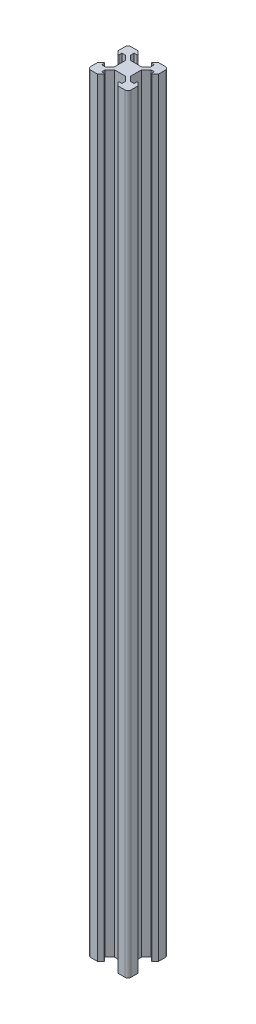
SolidWorks part; units mm, degrees
ref_plane "Спереди" through (0, 0, 0) normal (0, 0, 1) x (1, 0, 0)
ref_plane "Сверху" through (0, 0, 0) normal (0, 1, 0) x (1, 0, 0)
ref_plane "Справа" through (0, 0, 0) normal (1, 0, 0) x (0, 0, -1)
sketch "Эскиз1" plane through (0, 0, 0) normal (0, 1, 0) x (1, 0, 0)
  line L0 (8, 5) -> (6.2728, 5)
  line L1 (8.5, 10) -> (-8.5, 10)
  line L2 (10, 8.5) -> (10, -8.5)
  line L3 (8.5, -10) -> (-8.5, -10)
  line L4 (-10, 8.5) -> (-10, -8.5)
  line L5 (10, 10) -> (-10, -10) construction
  line L6 (10, -10) -> (-10, 10) construction
  line L7 (5, -10) -> (3.5121, -8.5121)
  line L8 (8, 5) -> (5, 5)
  line L9 (8, 5) -> (8, 3.7243)
  line L10 (8, -5) -> (6.2728, -5)
  line L11 (10, 5) -> (8.5121, 3.5121)
  line L12 (8, -5) -> (8, -3.7243)
  line L13 (10, 0) -> (-10, 0) construction
  line L14 (10, -5) -> (8.5121, -3.5121)
  line L15 (5, -8) -> (3.7243, -8)
  line L16 (5, -8) -> (5, -6.2728)
  line L17 (5, -6.2728) -> (2.7272, -4)
  line L18 (2.7272, -4) -> (-2.7272, -4)
  line L19 (-2.7272, -4) -> (-5, -6.2728)
  line L20 (-5, -8) -> (-5, -6.2728)
  line L21 (-5, -8) -> (-3.7243, -8)
  line L22 (-5, -10) -> (-3.5121, -8.5121)
  line L23 (-10, -5) -> (-8.5121, -3.5121)
  line L24 (-8, -5) -> (-8, -3.7243)
  line L25 (-8, -5) -> (-6.2728, -5)
  line L26 (-6.2728, -5) -> (-4, -2.7272)
  line L27 (-4, -2.7272) -> (-4, 2.7272)
  line L28 (-4, 2.7272) -> (-6.2728, 5)
  line L29 (-8, 5) -> (-6.2728, 5)
  line L30 (-8, 5) -> (-8, 3.7243)
  line L31 (-10, 5) -> (-8.5121, 3.5121)
  line L32 (-5, 10) -> (-3.5121, 8.5121)
  line L33 (-5, 8) -> (-3.7243, 8)
  line L34 (-5, 8) -> (-5, 6.2728)
  line L35 (-5, 6.2728) -> (-2.7272, 4)
  line L36 (6.2728, 5) -> (4, 2.7272)
  line L37 (-2.7272, 4) -> (2.7272, 4)
  line L38 (4, -2.7272) -> (6.2728, -5)
  line L39 (2.7272, 4) -> (5, 6.2728)
  line L40 (4, 2.7272) -> (4, -2.7272)
  line L41 (5, 8) -> (5, 6.2728)
  line L42 (5, 10) -> (5, 4) [skipped]
  line L43 (5, 8) -> (3, 8) [skipped]
  line L44 (5, 10) -> (3, 8) [skipped]
  line L45 (5, -10) -> (5, -4) [skipped]
  line L46 (5, -10) -> (3, -8) [skipped]
  line L47 (5, -8) -> (3, -8) [skipped]
  line L48 (-5, -10) -> (-5, -4) [skipped]
  line L49 (-5, -8) -> (-3, -8) [skipped]
  line L50 (-5, -10) -> (-3, -8) [skipped]
  line L51 (-10, -5) -> (-4, -5) [skipped]
  line L52 (-8, 5) -> (-8, 3) [skipped]
  line L53 (-10, 5) -> (-4, 5) [skipped]
  line L54 (-5, 10) -> (-5, 4) [skipped]
  line L55 (-5, 8) -> (-3, 8) [skipped]
  line L56 (-5, 10) -> (-3, 8) [skipped]
  line L57 (-10, 5) -> (-8, 3) [skipped]
  line L58 (-8, -5) -> (-8, -3) [skipped]
  line L59 (-10, -5) -> (-8, -3) [skipped]
  line L60 (5, 8) -> (3.7243, 8)
  line L61 (5, 10) -> (3.5121, 8.5121)
  arc A0 (-8.5, -10) -> (-10, -8.5) centre (-8.5, -8.5) cw
  arc A1 (-8.5, 10) -> (-10, 8.5) centre (-8.5, 8.5) ccw
  arc A2 (10, -8.5) -> (8.5, -10) centre (8.5, -8.5) cw
  arc A3 (8.5, 10) -> (10, 8.5) centre (8.5, 8.5) cw
  arc A4 (8, 3.7243) -> (8.5121, 3.5121) centre (8.3, 3.7243) ccw
  arc A5 (8, -3.7243) -> (8.5121, -3.5121) centre (8.3, -3.7243) cw
  arc A6 (-8, 3.7243) -> (-8.5121, 3.5121) centre (-8.3, 3.7243) cw
  arc A7 (-8.5121, -3.5121) -> (-8, -3.7243) centre (-8.3, -3.7243) cw
  arc A8 (-3.7243, -8) -> (-3.5121, -8.5121) centre (-3.7243, -8.3) cw
  arc A9 (3.5121, -8.5121) -> (3.7243, -8) centre (3.7243, -8.3) cw
  arc A10 (3.7243, 8) -> (3.5121, 8.5121) centre (3.7243, 8.3) cw
  arc A11 (-3.7243, 8) -> (-3.5121, 8.5121) centre (-3.7243, 8.3) ccw
  point P0 (0, 0)
  point P12 (4, 0)
  point P20 (0, 0)
  point P21 (0, 0)
  point P29 (0, 0)
  point P33 (0, 0)
  point P38 (0, 0)
  point P45 (0, 0)
  point P47 (0, 0)
  point P96 (0, 0)
  point P108 (8, 3)
  point P111 (8, -3)
  dimension "D13" = 1.5
  dimension "D14" = 0.3
  dimension "D1" = 3
  dimension "D2" = 2
  dimension "D3" = 5
  dimension "D4" = 6
  dimension "D5" = 20
  dimension "D6" = 20
  dimension "D8" = 0.9
  dimension "D9" = 0.9
  dimension "D10" = 3.7272
  dimension "D11" = 5
  dimension "D7" = 4
  dimension "D12" = 4
extrude "Бобышка-Вытянуть1" add sketch "Эскиз1" along normal blind 380
